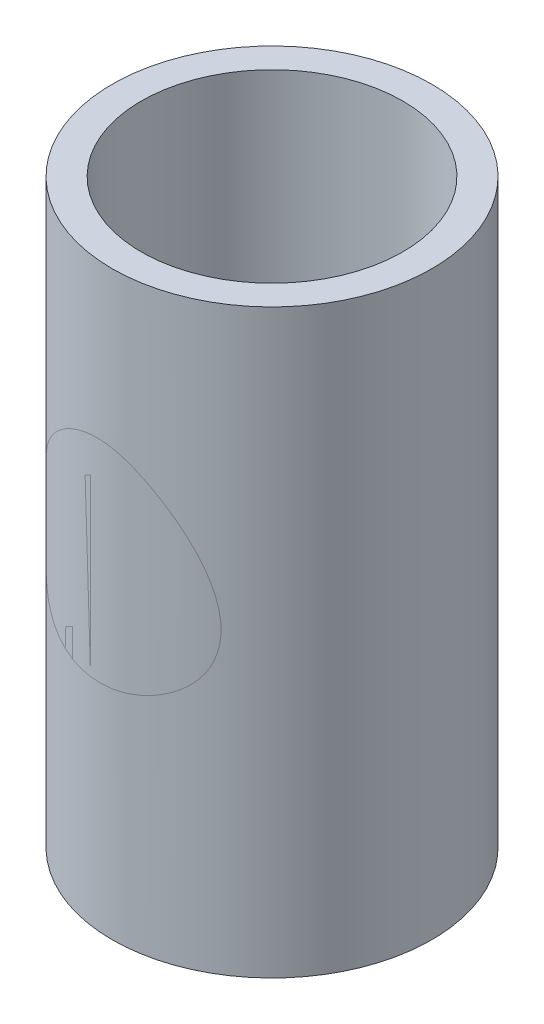
SolidWorks part; units mm, degrees
ref_plane "Спереди" through (0, 0, 0) normal (0, 0, 1) x (1, 0, 0)
ref_plane "Сверху" through (0, 0, 0) normal (0, 1, 0) x (1, 0, 0)
ref_plane "Справа" through (0, 0, 0) normal (1, 0, 0) x (0, 0, -1)
sketch "Эскиз1" plane through (0, 0, 0) normal (0, 0, 1) x (1, 0, 0)
  line L0 (0, -110.6031) -> (0, 130.0787) construction
  line L1 (45, 100) -> (55, 100)
  line L2 (45, 100) -> (45, -100)
  line L3 (45, -100) -> (55, -100)
  line L4 (55, 100) -> (55, -100)
  point P4 (45, 0)
  dimension "D1" = 10
  dimension "D2" = 200
  dimension "D3" = 45
revolve "Повернуть1" add sketch "Эскиз1" angle 360 about L0
ref_plane "Плоскость1" through (0, 0, 55) normal (0, 0, 1) x (1, 0, 0)
sketch "Эскиз2" plane through (0, 0, 55) normal (0, 0, 1) x (1, 0, 0)
  spline S0 degree 3 poles (-54.6404, -30.9953) (-37.7126, 28.6116) (8.4641, 64.6749) (54.8948, -29.3483) (-54.6404, -30.9953) (-37.7126, 28.6116) (8.4641, 64.6749) knots -0.813776 -0.511938 -0.19742 0 0.186224 0.488062 0.80258 1 1.186224 1.488062 1.80258 only from (-33.0608, 26.2387) to (-33.0608, 26.2387)
split line "Разделяющая линия1"
surface "Поверхность-Сместить1" parameters "D1"=0
